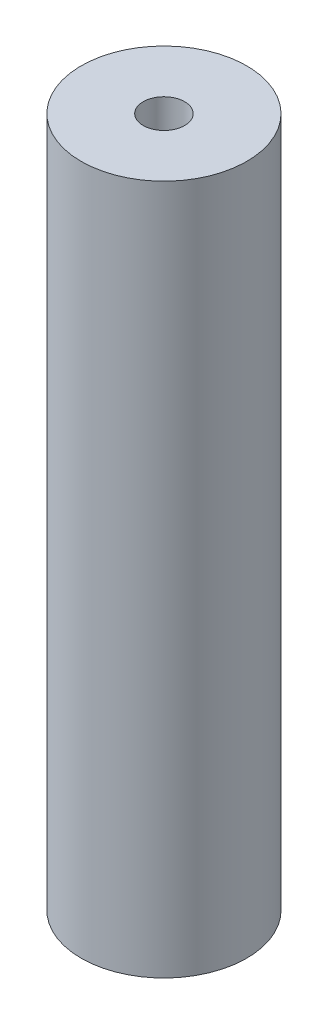
SolidWorks part; units mm, degrees
ref_plane "Front Plane" through (0, 0, 0) normal (0, 0, 1) x (1, 0, 0)
ref_plane "Top Plane" through (0, 0, 0) normal (0, 1, 0) x (1, 0, 0)
ref_plane "Right Plane" through (0, 0, 0) normal (1, 0, 0) x (0, 0, -1)
sketch "Sketch1" plane through (0, 0, 0) normal (0, 1, 0) x (1, 0, 0)
  circle A0 centre (0, 0) radius 6
  dimension "D1" = 12
extrude "Boss-Extrude1" add sketch "Sketch1" along normal blind 50
hole_wizard "#32 (0.116) Diameter Hole1" positions "Sketch3" profile "Sketch2" hole size "#32" standard "ANSI Inch"
sketch "Sketch3" plane through (0, 50, 0) normal (0, 1, 0) x (1, 0, 0)
  point P0 (0, 0)
sketch "Sketch2" plane through (0, 50, 0) normal (1, 0, 0) x (0, 0, 1)
  line L0 (0, 0) -> (0, 10.9013)
  line L1 (0, 10.9013) -> (1.5, 10)
  line L2 (1.5, 10) -> (1.5, 0)
  line L5 (1.5, 0) -> (0, 0)
  line L10 (0, 10.9013) -> (-1.5, 10) construction
  line L11 (0, -6.35) -> (0, 107.95) construction
  dimension "Hole Dia." = 3
  dimension "Hole Depth" = 10
  dimension "Drill Angle" = 118
